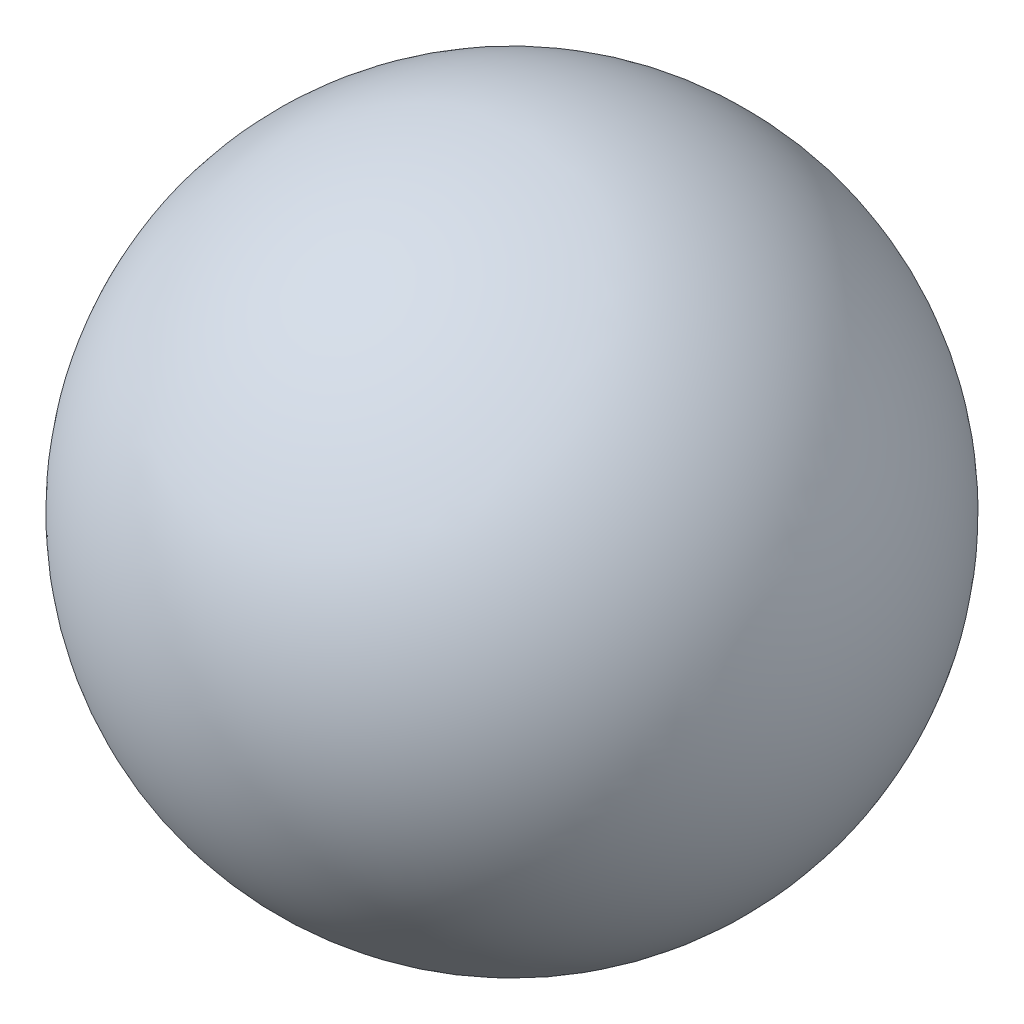
SolidWorks part; units mm, degrees
ref_plane "Front Plane" through (0, 0, 0) normal (0, 0, 1) x (1, 0, 0)
ref_plane "Top Plane" through (0, 0, 0) normal (0, 1, 0) x (1, 0, 0)
ref_plane "Right Plane" through (0, 0, 0) normal (1, 0, 0) x (0, 0, -1)
sketch "Sketch1" plane through (0, 0, 0) normal (0, 0, 1) x (1, 0, 0)
  line L0 (-30.1156, 0) -> (30.1156, 0)
  arc A0 (30.1156, 0) -> (-30.1156, 0) centre (0, 0) ccw
revolve "Revolve1" add sketch "Sketch1" angle 360 about L0
